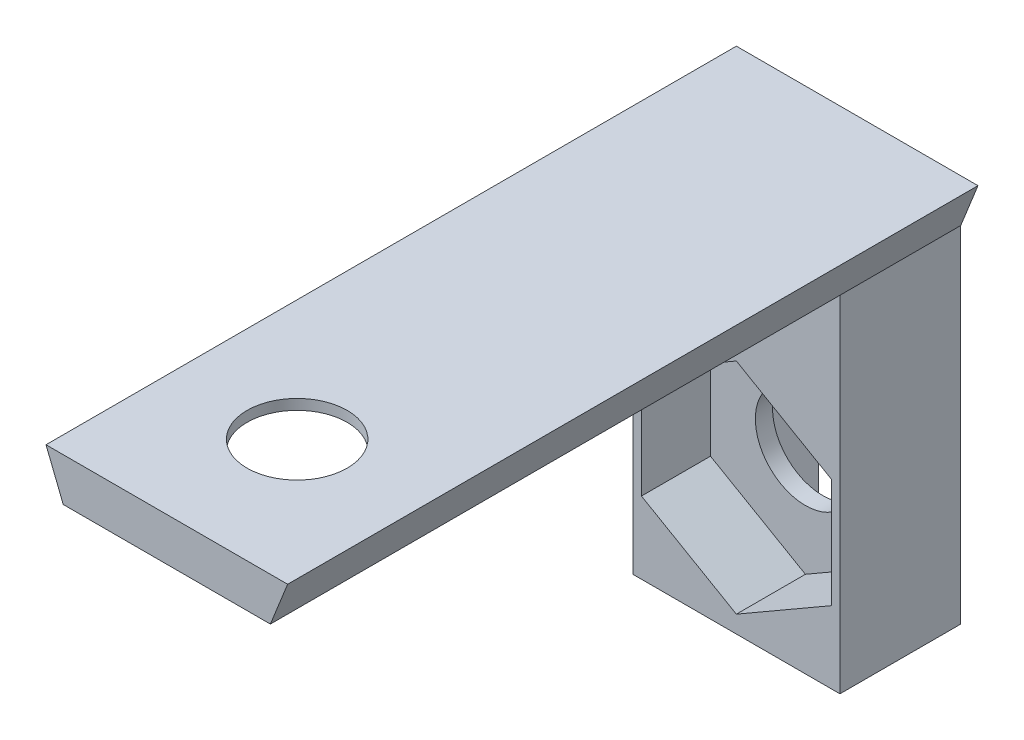
SolidWorks part; units mm, degrees
ref_plane "Front Plane" through (0, 0, 0) normal (0, 0, 1) x (1, 0, 0)
ref_plane "Top Plane" through (0, 0, 0) normal (0, 1, 0) x (1, 0, 0)
ref_plane "Right Plane" through (0, 0, 0) normal (1, 0, 0) x (0, 0, -1)
sketch "Sketch1" plane through (0, 0, 0) normal (0, 1, 0) x (1, 0, 0)
  line L1 (-6, -3.5) -> (6, -3.5)
  line L2 (-6, -3.5) -> (-6, 3.5)
  line L3 (-6, 3.5) -> (6, 3.5)
  line L4 (6, -3.5) -> (6, 3.5)
  line L5 (-6, -3.5) -> (6, 3.5) construction
  line L6 (-6, 3.5) -> (6, -3.5) construction
  point P0 (0, 0)
extrude "Boss-Extrude1" add sketch "Sketch1" along normal blind 20
sketch "Sketch2" plane through (0, 20, 0) normal (0, 1, 0) x (1, 0, 0)
  line L0 (0, 3.5) -> (0, 1.5) construction
  line L1 (6, 3.5) -> (-6, 3.5) construction
  line L22 (0, 3.5) -> (2.25, 3.5)
  line L23 (0, 3.5) -> (-2.25, 3.5)
  line L25 (0, 1.5) -> (4.25, 1.5)
  line L27 (0, 1.5) -> (-4.25, 1.5)
  line L28 (-4.25, 1.5) -> (-2.25, 3.5)
  line L29 (2.25, 3.5) -> (4.25, 1.5)
extrude "Cut-Extrude1" cut sketch "Sketch2" against normal blind 20
sketch "Sketch3" plane through (0, 0, 3.5) normal (0, 0, 1) x (1, 0, 0)
  line L0 (0, 0) -> (0, 7.35) construction
  line L1 (-6, 0) -> (6, 0) construction
  circle A0 centre (0, 7.35) radius 2.9
  point P2 (0, 7.705)
extrude "Cut-Extrude2" cut sketch "Sketch3" against normal up to next
sketch "Sketch4" plane through (0, 0, 3.5) normal (0, 0, 1) x (1, 0, 0)
  line L0 (0, 0) -> (0, 7.35) construction
  line L1 (0, 13.7009) -> (-5.5, 10.5254)
  line L2 (-5.5, 10.5254) -> (-5.5, 4.1746)
  line L3 (-5.5, 4.1746) -> (0, 0.9991)
  line L4 (0, 0.9991) -> (5.5, 4.1746)
  line L5 (5.5, 4.1746) -> (5.5, 10.5254)
  line L6 (5.5, 10.5254) -> (0, 13.7009)
  circle A0 centre (0, 7.35) radius 5.5 construction
  point P1 (0, 0)
  point P13 (0, 0)
  point P14 (0, 7.5275)
extrude "Cut-Extrude3" cut sketch "Sketch4" against normal blind 4
sketch "Sketch5" plane through (0, 20, 0) normal (0, 1, 0) x (1, 0, 0)
  line L0 (-6, 3.5) -> (-7, 3.5) construction
  line L1 (6, 3.5) -> (7, 3.5) construction
  line L3 (-7, 3.5) -> (7, 3.5)
  line L4 (-7, 3.5) -> (-7, -36.5)
  line L5 (-7, -36.5) -> (7, -36.5)
  line L6 (7, 3.5) -> (7, -36.5)
extrude "Boss-Extrude2" add sketch "Sketch5" along normal blind 2.5
sketch "Sketch6" plane through (0, 0, -3.5) normal (0, 0, -1) x (-1, 0, 0)
  line L0 (-7, 20) -> (-7, 22.5)
  line L1 (-7, 22.5) -> (-6, 20)
  line L2 (-6, 20) -> (-7, 20)
  line L3 (7, 20) -> (6, 20)
  line L4 (6, 20) -> (7, 22.5)
  line L5 (7, 22.5) -> (7, 20)
extrude "Cut-Extrude4" cut sketch "Sketch6" against normal up to next
sketch "Sketch8" plane through (0, 20, 0) normal (0, -1, 0) x (1, 0, 0)
  line L1 (0, 22.5991) -> (5.5, 25.7746)
  line L2 (5.5, 25.7746) -> (5.5, 32.1254)
  line L3 (5.5, 32.1254) -> (0, 35.3009)
  line L4 (0, 35.3009) -> (-5.5, 32.1254)
  line L5 (-5.5, 32.1254) -> (-5.5, 25.7746)
  line L6 (-5.5, 25.7746) -> (0, 22.5991)
  line L7 (0, 36.5) -> (0, 28.95) construction
  line L8 (-6, 36.5) -> (6, 36.5) construction
  circle A0 centre (0, 28.95) radius 5.5 construction
extrude "Cut-Extrude6" cut sketch "Sketch8" against normal blind 1.9
sketch "Sketch9" plane through (0, 21.9, 0) normal (0, -1, 0) x (-1, 0, 0)
  circle A0 centre (0, -28.95) radius 2.9
extrude "Cut-Extrude7" cut sketch "Sketch9" against normal up to next
